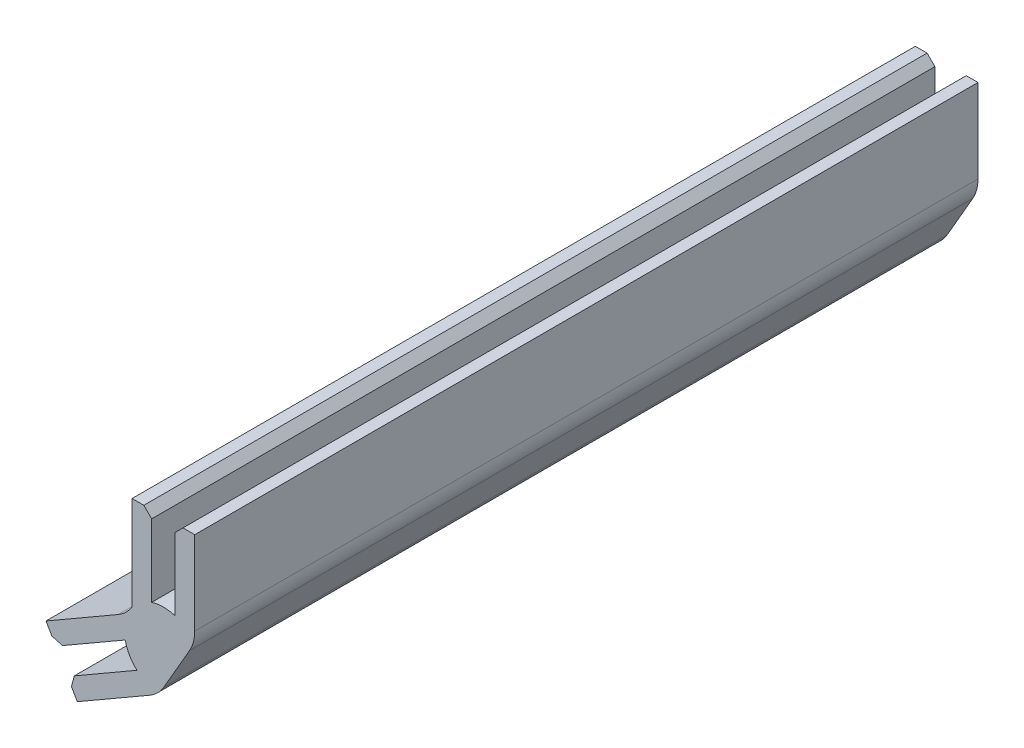
SolidWorks part; units mm, degrees
ref_plane "前视基准面" through (0, 0, 0) normal (0, 0, 1) x (1, 0, 0)
ref_plane "上视基准面" through (0, 0, 0) normal (0, 1, 0) x (1, 0, 0)
ref_plane "右视基准面" through (0, 0, 0) normal (1, 0, 0) x (0, 0, -1)
other "Configuration Table"
sketch "草图2" plane through (0, 0, 0) normal (0, 0, 1) x (1, 0, 0)
  line L1 (0, 0) -> (0, 54.5652) construction
  line L8 (1.5, 4.7697) -> (1.5, 15)
  line L12 (-4, 3) -> (-4, 15)
  line L19 (-4, 15) -> (-1.5, 15)
  line L21 (-1.5, 4.7697) -> (-1.5, 15)
  line L25 (4, 15) -> (1.5, 15)
  line L26 (4, 3) -> (4, 15)
  line L27 (-4.8807, -1.0858) -> (-13.7404, -6.201)
  line L28 (-0.5981, -4.9641) -> (-10.9904, -10.9641)
  line L29 (-10.9904, -10.9641) -> (-12.2404, -8.799)
  line L30 (-3.3807, -3.6839) -> (-12.2404, -8.799)
  line L31 (-14.9904, -4.0359) -> (-13.7404, -6.201)
  line L32 (-4.5981, 1.9641) -> (-14.9904, -4.0359)
  line L33 (0, 0) -> (-47.2548, -27.2826) construction
  arc A12 (-4.8807, -1.0858) -> (-3.3807, -3.6839) centre (0, 0) ccw
  arc A13 (-0.5981, -4.9641) -> (4, 3) centre (0, 0) ccw
  arc A14 (-4, 3) -> (-4.5981, 1.9641) centre (0, 0) ccw
  arc A15 (1.5, 4.7697) -> (-1.5, 4.7697) centre (0, 0) ccw
  point P15 (0, 0)
  point P25 (0, 0)
  dimension "D1" = 10
  dimension "D2" = 15
  dimension "D3" = 2.5
  dimension "D4" = 3
  dimension "D5" = 2
  dimension "D6" = 120
extrude "凸台-拉伸1" add sketch "草图2" along normal blind 100
sketch "草图5" plane through (0, 0, 100) normal (0, 0, 1) x (1, 0, 0)
  line L0 (4, 3) -> (-0.5981, -4.9641)
  line L1 (-10.9904, -10.9641) -> (-0.5981, -4.9641) construction
  arc A0 (-0.5981, -4.9641) -> (4, 3) centre (0, 0) ccw construction
  arc A1 (-0.5981, -4.9641) -> (4, 3) centre (0, 0) ccw
extrude "切除-拉伸2" cut sketch "草图5" against normal through all
fillet "圆角2" radius 5 3 edges at (4, 3, 50) (-0.5981, -4.9641, 50) (-4.5981, 1.9641, 50)
chamfer "倒角1" distance 1 angle 45 4 edges at (1.5, 15, 50) (-1.5, 15, 50) (-12.2404, -8.799, 50) (-13.7404, -6.201, 50)
